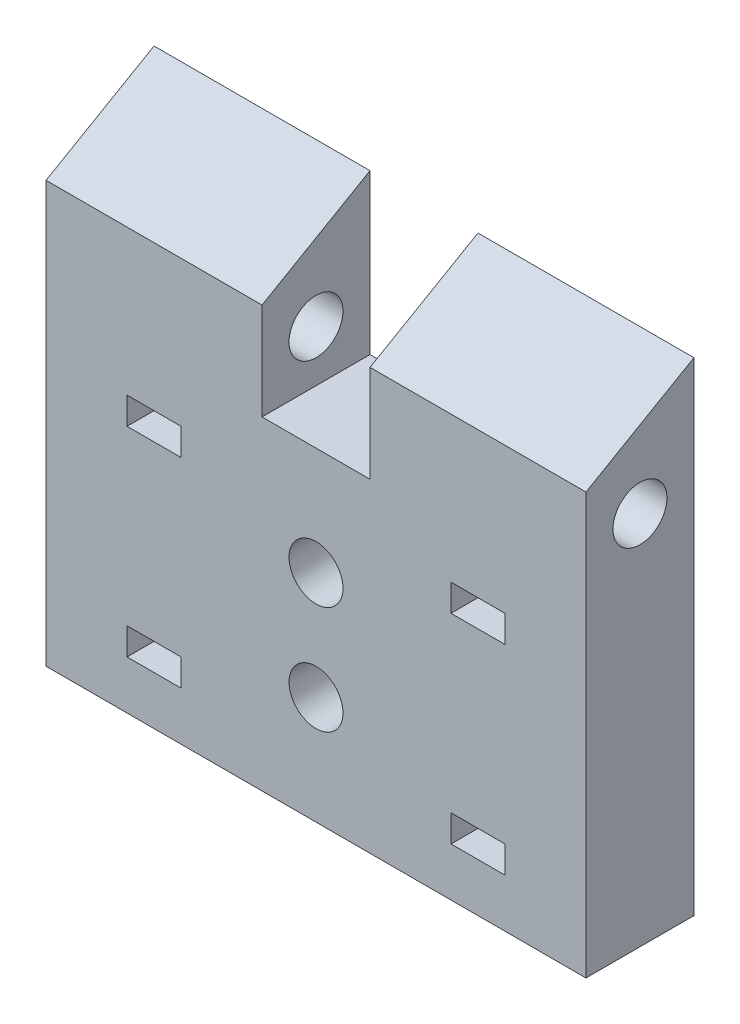
SolidWorks part; units mm, degrees
ref_plane "Plan de face" through (0, 0, 0) normal (0, 0, 1) x (1, 0, 0)
ref_plane "Plan de dessus" through (0, 0, 0) normal (0, 1, 0) x (1, 0, 0)
ref_plane "Plan de droite" through (0, 0, 0) normal (1, 0, 0) x (0, 0, -1)
sketch "Esquisse1" plane through (0, 0, 0) normal (0, 0, 1) x (1, 0, 0)
  line L0 (-25, -15) -> (-5, -15)
  line L1 (-5, -15) -> (5, -15)
  line L2 (0, -15) -> (0, 15) construction
  line L3 (-5, 15) -> (5, 15)
  line L4 (25, -15) -> (25, 29.75)
  line L5 (-5, -15) -> (5, 15) construction
  line L6 (-5, 15) -> (5, -15) construction
  line L7 (5, 29.75) -> (25, 29.75)
  line L8 (-5, 15) -> (-5, 29.75)
  line L9 (-5, 29.75) -> (-25, 29.75)
  line L10 (-25, -15) -> (-25, 29.75)
  line L11 (5, 15) -> (5, 29.75)
  line L12 (25, -15) -> (5, -15)
  circle A0 centre (0, -5) radius 2.5
  circle A1 centre (0, 5) radius 2.5
  point P0 (0, 3.5555)
  dimension "D3" = 10
  dimension "D4" = 5
  dimension "D11" = 5
  dimension "D1" = 30
  dimension "D2" = 10
  dimension "D5" = 5
  dimension "D6" = 20
extrude "Boss.-Extru.1" add sketch "Esquisse1" along normal blind 10
sketch "Esquisse2" plane through (-25, 0, 0) normal (-1, 0, 0) x (0, 0, 1)
  line L0 (0, 29.75) -> (10, 29.75)
  line L1 (10, 29.75) -> (10, 23.9765)
  line L2 (10, -15) -> (10, 29.75) construction
  line L3 (10, 23.9765) -> (0, 29.75)
  line L4 (0, 29.75) -> (10, 9.75) construction
  line L5 (10, -15) -> (10, 29.75) construction
  circle A0 centre (5, 19.75) radius 2.5
  point P10 (10, 15)
  point P11 (10, 10.4277)
  dimension "D2" = 5
  dimension "D1" = 30
  dimension "D3" = 10
extrude "Enlèv. mat.-Extru.1" cut sketch "Esquisse2" against normal up to surface (50 mm away) up to face at (25, 7.375, 5)
sketch "Esquisse3" plane through (0, 0, 10) normal (0, 0, 1) x (1, 0, 0)
  line L0 (-5, 15) -> (-5, -15) construction
  line L1 (25, -15) -> (-25, -15) construction
  line L2 (-5, -15) -> (-25, 23.9765) construction
  line L3 (-25, 23.9765) -> (-15, 23.9765) construction
  line L4 (-5, 23.9765) -> (-25, 23.9765) construction
  line L5 (-15, 23.9765) -> (-15, -15) construction
  line L6 (-17.5, 10.5) -> (-12.5, -10.5) construction
  line L7 (-17.5, 8) -> (-12.5, 8)
  line L8 (-17.5, 8) -> (-17.5, 10.5)
  line L9 (-17.5, 10.5) -> (-12.5, 10.5)
  line L10 (-12.5, 8) -> (-12.5, 10.5)
  line L11 (-17.5, 8) -> (-12.5, 10.5) construction
  line L12 (-17.5, 10.5) -> (-12.5, 8) construction
  line L13 (-17.5, -10.5) -> (-12.5, -10.5)
  line L14 (-17.5, -10.5) -> (-17.5, -8)
  line L15 (-17.5, -8) -> (-12.5, -8)
  line L16 (-12.5, -10.5) -> (-12.5, -8)
  line L17 (-17.5, -10.5) -> (-12.5, -8) construction
  line L18 (-17.5, -8) -> (-12.5, -10.5) construction
  line L19 (-17.5, -10.5) -> (-12.5, 10.5) construction
  line L20 (0, 5) -> (0, -5) construction
  line L21 (0, -5) -> (0, 0) construction
  line L22 (0, 0) -> (-15, 0) construction
  line L23 (17.5, -10.5) -> (12.5, 10.5) construction
  line L24 (17.5, -8) -> (12.5, -10.5) construction
  line L25 (17.5, -10.5) -> (12.5, -8) construction
  line L26 (17.5, 10.5) -> (12.5, 8) construction
  line L27 (17.5, 8) -> (12.5, 10.5) construction
  line L28 (17.5, 10.5) -> (12.5, -10.5) construction
  line L29 (12.5, -10.5) -> (12.5, -8)
  line L30 (17.5, -8) -> (12.5, -8)
  line L31 (17.5, -10.5) -> (17.5, -8)
  line L32 (17.5, -10.5) -> (12.5, -10.5)
  line L33 (12.5, 8) -> (12.5, 10.5)
  line L34 (17.5, 10.5) -> (12.5, 10.5)
  line L35 (17.5, 8) -> (17.5, 10.5)
  line L36 (17.5, 8) -> (12.5, 8)
  point P11 (-15, 9.25)
  point P16 (-15, -9.25)
  point P21 (0, 5)
  point P22 (0, -5)
  point P38 (15, -9.25)
  point P39 (15, 9.25)
  dimension "D1" = 2.5
  dimension "D2" = 5
  dimension "D3" = 2.5
  dimension "D4" = 5
  dimension "D5" = 8
extrude "Enlèv. mat.-Extru.2" cut sketch "Esquisse3" against normal up to surface (10 mm away) up to face at (2.5, 5, 0)
